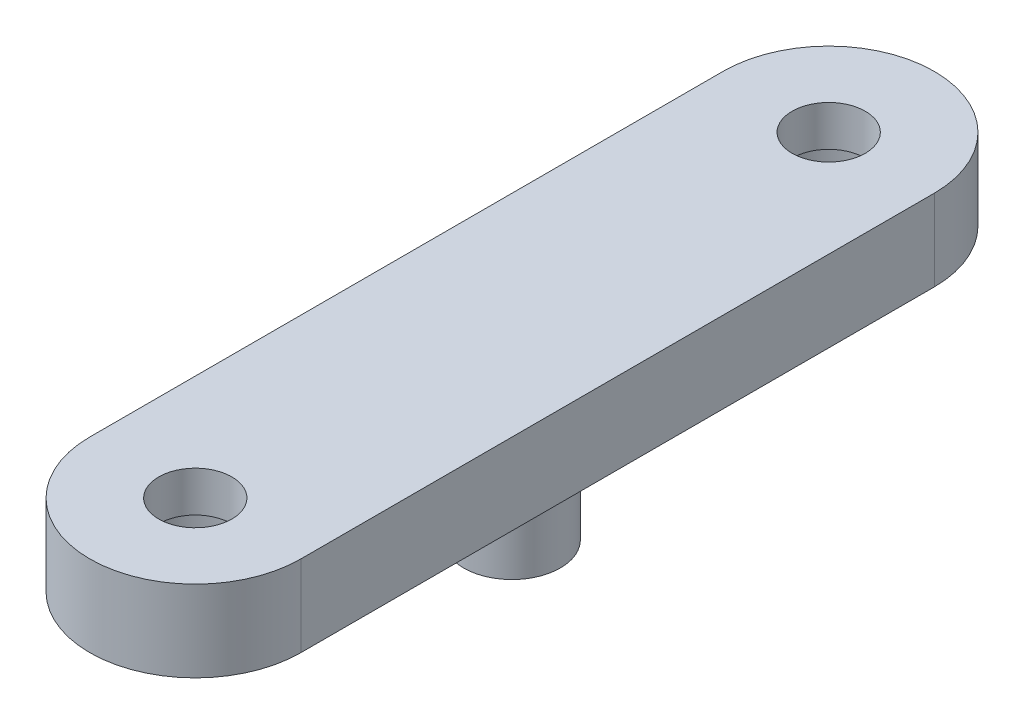
SolidWorks part; units mm, degrees
material "Aleación 6061"
ref_plane "Alzado" through (0, 0, 0) normal (0, 0, 1) x (1, 0, 0)
ref_plane "Planta" through (0, 0, 0) normal (0, 1, 0) x (1, 0, 0)
ref_plane "Vista lateral" through (0, 0, 0) normal (1, 0, 0) x (0, 0, -1)
sketch "Sk_Barra" plane through (0, 0, 0) normal (0, 1, 0) x (1, 0, 0)
  line L1 (-6.5, -349.5) -> (6.5, -349.5)
  line L2 (-6.5, -349.5) -> (-6.5, -310.5)
  line L3 (-6.5, -310.5) -> (6.5, -310.5)
  line L4 (6.5, -349.5) -> (6.5, -310.5)
  line L5 (-6.5, -349.5) -> (6.5, -310.5) construction
  line L6 (-6.5, -310.5) -> (6.5, -349.5) construction
  point P0 (0, -330)
  dimension "D1" = 13
  dimension "D2" = 39
  dimension "D3" = 330
extrude "Barra" add sketch "Sk_Barra" along normal blind 5 from offset 57.75
sketch "Sk_Extremos" plane through (0, 0, 0) normal (0, 1, 0) x (1, 0, 0)
  circle A0 centre (0, -310.5) radius 6.5
  circle A1 centre (0, -349.5) radius 6.5
  dimension "D1" = 13
  dimension "D3" = 13
  dimension "D2" = 310.5
  dimension "D4" = 349.5
extrude "Extremos" add sketch "Sk_Extremos" along normal blind 5 from offset 57.75
sketch "Sk_Perno_696" plane through (0, 0, 0) normal (0, 1, 0) x (1, 0, 0)
  circle A0 centre (0, -330) radius 2.975
  dimension "D1" = 5.95
  dimension "D2" = 330
extrude "Perno_696" add sketch "Sk_Perno_696" along normal blind 7 from offset 64.75
sketch "Sk_Pasantes_M4" plane through (0, 0, 0) normal (0, 1, 0) x (1, 0, 0)
  circle A0 centre (0, -310.5) radius 2.25
  circle A1 centre (0, -349.5) radius 2.25
  dimension "D1" = 4.5
  dimension "D3" = 4.5
  dimension "D2" = 310.5
  dimension "D4" = 349.5
extrude "Pasantes_M4" cut sketch "Sk_Pasantes_M4" along normal blind 5 from offset 57.75
sketch "Sk_Avellanado_M4" plane through (0, 0, 0) normal (0, 1, 0) x (1, 0, 0)
  circle A0 centre (0, -310.5) radius 4.2
  circle A1 centre (0, -349.5) radius 4.2
  dimension "D1" = 8.4
  dimension "D3" = 8.4
  dimension "D2" = 310.5
  dimension "D4" = 349.5
extrude "Avellanado_M4" cut sketch "Sk_Avellanado_M4" along normal blind 2.5 from offset 57.75
